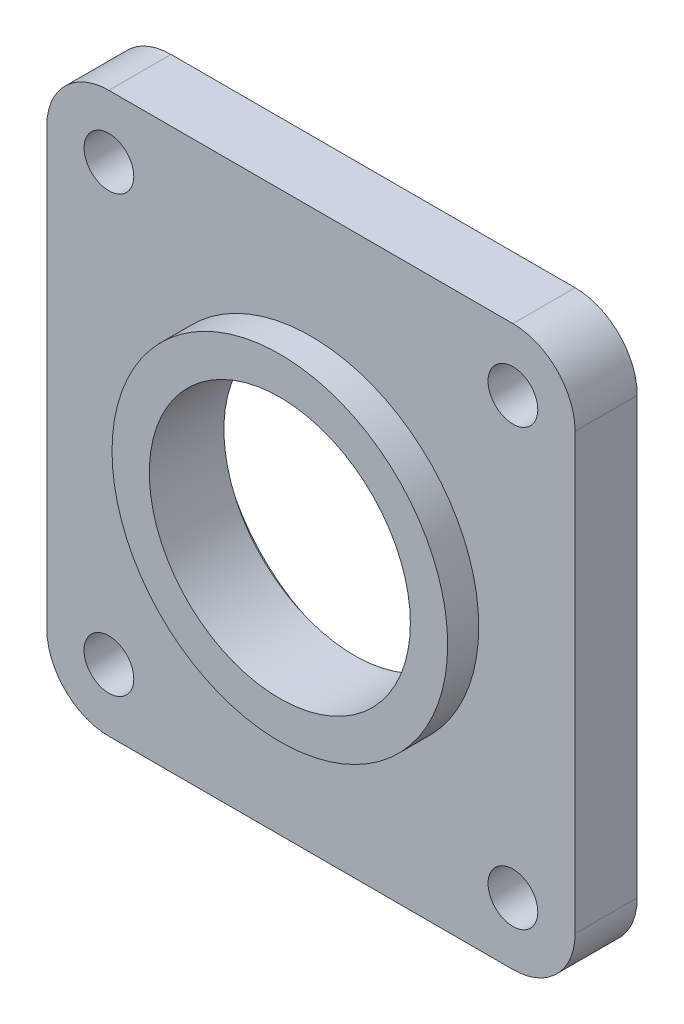
SolidWorks part; units mm, degrees
ref_plane "Płaszczyzna przednia" through (0, 0, 0) normal (0, 0, 1) x (1, 0, 0)
ref_plane "Płaszczyzna górna" through (0, 0, 0) normal (0, 1, 0) x (1, 0, 0)
ref_plane "Płaszczyzna prawa" through (0, 0, 0) normal (1, 0, 0) x (0, 0, -1)
sketch "Szkic1" plane through (0, 0, 0) normal (0, 0, 1) x (1, 0, 0)
  line L1 (-42.5, 45) -> (42.5, 45)
  line L2 (-42.5, 45) -> (-42.5, -45)
  line L3 (-42.5, -45) -> (42.5, -45)
  line L4 (42.5, 45) -> (42.5, -45)
  line L5 (-42.5, 45) -> (42.5, -45) construction
  line L6 (-42.5, -45) -> (42.5, 45) construction
  point P0 (0, 0)
  dimension "D1" = 85
  dimension "D2" = 90
extrude "Dodanie-wyciągnięcie1" add sketch "Szkic1" along normal blind 10
sketch "Szkic2" plane through (0, 0, 0) normal (0, 1, 0) x (1, 0, 0)
  line L0 (0, 0) -> (25, 0)
  line L1 (25, 0) -> (25, -3)
  line L2 (25, -3) -> (21, -3)
  line L3 (21, -3) -> (21, -10)
  line L4 (21, -10) -> (0, -10)
  line L5 (0, -10) -> (0, 0)
  line L6 (0, 0) -> (0, 6.3733) construction
  dimension "D1" = 50
  dimension "D2" = 42
  dimension "D3" = 3
  dimension "D4" = 7
revolve "Wycięcie-obrót1" cut sketch "Szkic2" angle 360 about L6
sketch "Szkic9" plane through (0, 0, 10) normal (0, 0, 1) x (1, 0, 0)
  circle A0 centre (0, 0) radius 21 construction
  circle A1 centre (0, 0) radius 21
  circle A2 centre (0, 0) radius 27
  dimension "D1" = 6
extrude "Dodanie-wyciągnięcie2" add sketch "Szkic9" along normal blind 5
fillet "Zaokrąglenie1" radius 10 4 edges at (42.5, 45, 5) (-42.5, 45, 5) (-42.5, -45, 5) (42.5, -45, 5)
hole_wizard "Pogłębienie stożkowe pod M6 Wkręt ustalający1" positions "Szkic10" profile "Szkic11" countersink size "M6" standard "Ansi Metric"
sketch "Szkic10" plane through (267.5, 155, -16) normal (0, 0, -1) x (1, 0, 0)
  line L2 (-300, 200) -> (-235, 200)
  line L3 (-225, 190) -> (-225, 120)
  line L4 (-300, 200) -> (-235, 200)
  line L5 (-225, 190) -> (-225, 120)
  point P0 (-235, 190)
  point P8 (-235, 120)
  point P10 (-300, 120)
  point P12 (-300, 190)
sketch "Szkic11" plane through (32.5, -35, -16) normal (1, 0, 0) x (0, 1, 0)
  line L0 (0, 0) -> (0, 27.9228)
  line L1 (0, 27.9228) -> (3.2, 26)
  line L2 (3.2, 26) -> (3.2, 3.52)
  line L3 (3.2, 3.52) -> (6.72, 0)
  line L4 (6.72, 0) -> (0, 0)
  line L5 (-3.2, 3.52) -> (-6.72, 0) construction
  line L6 (0, 27.9228) -> (-3.2, 26) construction
  line L7 (0, -6.35) -> (0, 107.95) construction
  dimension "Średnica otworu" = 6.4
  dimension "Głębokośc otworu" = 26
  dimension "Średnica zewnętrznego pogłębienia stożkowego" = 13.44
  dimension "Kąt zewnętrznego pogłębienia stożkowego" = 90
  dimension "Kąt wiertła" = 118
sketch "Szkic12" plane through (0, 0, 0) normal (0, 0, -1) x (-1, 0, 0)
  circle A0 centre (-32.5, 35) radius 3.2 construction
  circle A1 centre (32.5, 35) radius 3.2 construction
  circle A2 centre (32.5, -35) radius 3.2 construction
  circle A3 centre (-32.5, -35) radius 3.2 construction
  circle A4 centre (-32.5, 35) radius 3.2 construction
  circle A5 centre (32.5, 35) radius 3.2 construction
  circle A6 centre (32.5, -35) radius 3.2 construction
  circle A7 centre (-32.5, -35) radius 3.2 construction
  circle A8 centre (-32.5, 35) radius 4
  circle A9 centre (32.5, 35) radius 4
  circle A10 centre (32.5, -35) radius 4
  circle A11 centre (-32.5, -35) radius 4
  dimension "D1" = 8
extrude "Wytnij-wyciągnięcie2" cut sketch "Szkic12" against normal through all
